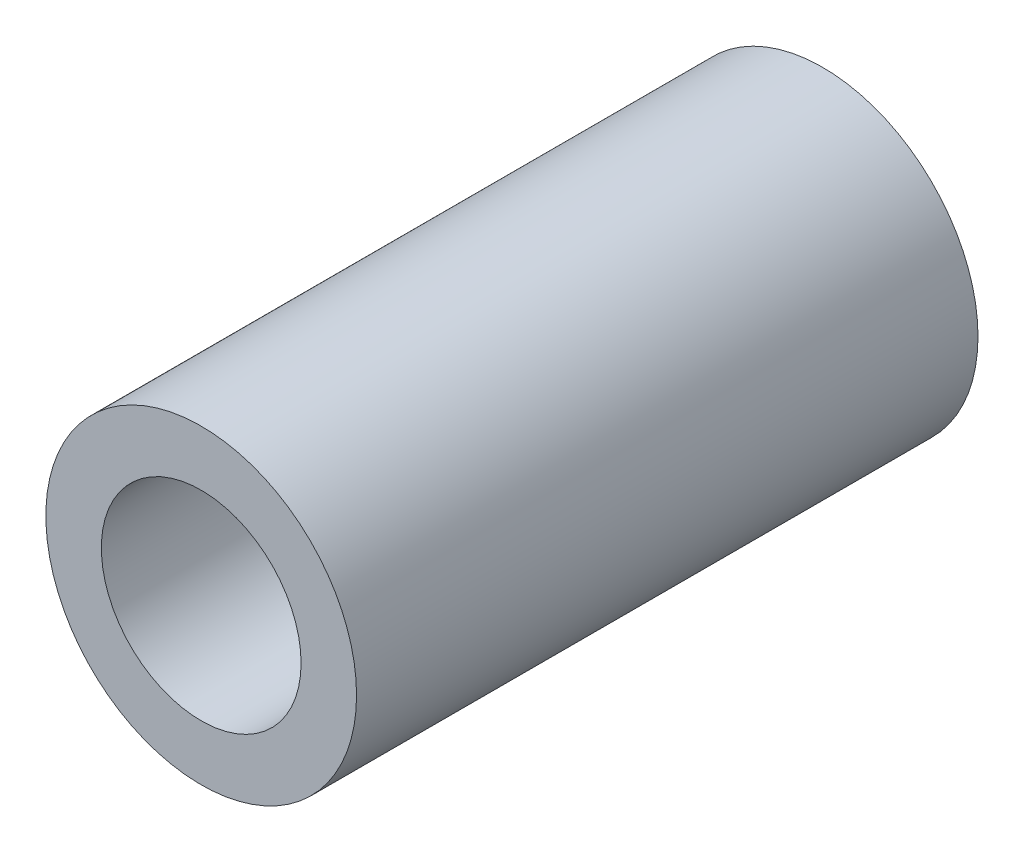
SolidWorks part; units mm, degrees
ref_plane "Alzado" through (0, 0, 0) normal (0, 0, 1) x (1, 0, 0)
ref_plane "Planta" through (0, 0, 0) normal (0, 1, 0) x (1, 0, 0)
ref_plane "Vista lateral" through (0, 0, 0) normal (1, 0, 0) x (0, 0, -1)
sketch "Croquis1" plane through (0, 0, 0) normal (0, 0, 1) x (1, 0, 0)
  circle A0 centre (0, 0) radius 7
  circle A1 centre (0, 0) radius 4.5
  dimension "D1" = 9
  dimension "D2" = 14
extrude "Saliente-Extruir1" add sketch "Croquis1" along normal blind 28
